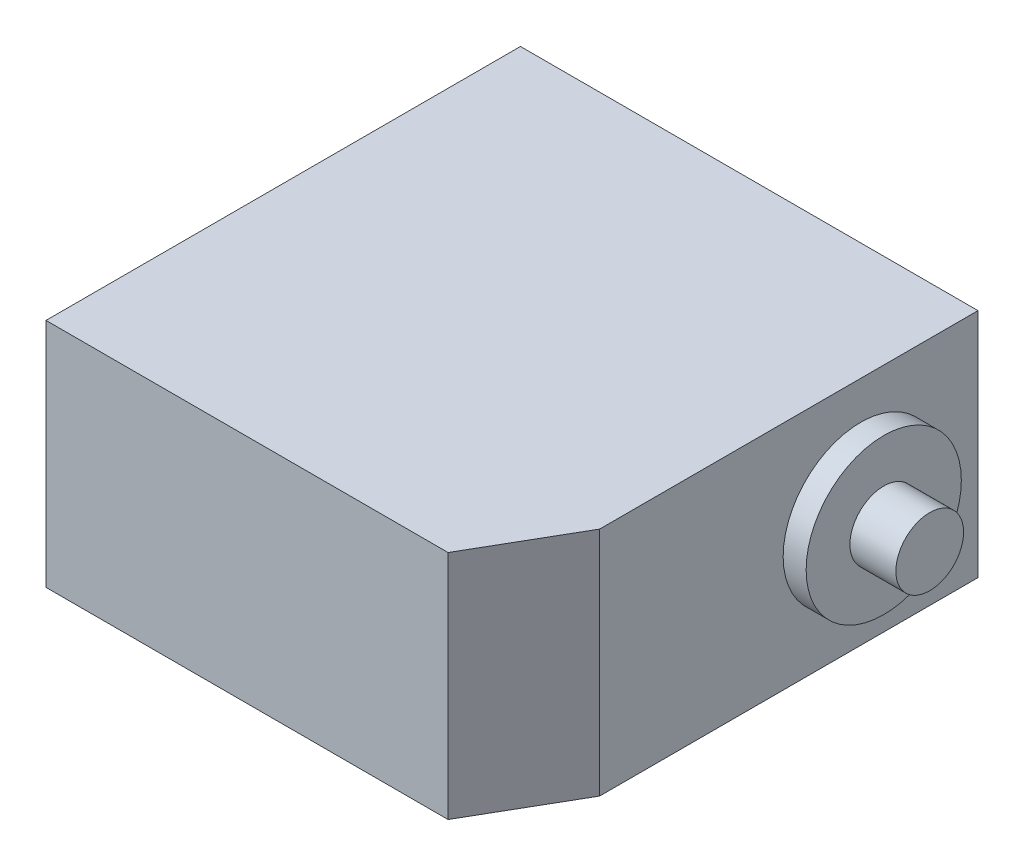
SolidWorks part; units mm, degrees
ref_plane "Front Plane" through (0, 0, 0) normal (0, 0, 1) x (1, 0, 0)
ref_plane "Top Plane" through (0, 0, 0) normal (0, 1, 0) x (1, 0, 0)
ref_plane "Right Plane" through (0, 0, 0) normal (1, 0, 0) x (0, 0, -1)
sketch "Sketch1" plane through (0, 0, 0) normal (0, 1, 0) x (1, 0, 0)
  line L0 (19.9009, -12.2786) -> (15.0749, -20.6375)
  line L1 (-19.9009, -20.6375) -> (15.0749, -20.6375)
  line L2 (-19.9009, -20.6375) -> (-19.9009, 20.6375)
  line L3 (-19.9009, 20.6375) -> (19.9009, 20.6375)
  line L4 (19.9009, -12.2786) -> (19.9009, 20.6375)
  line L5 (-19.9009, -20.6375) -> (19.9009, 20.6375) construction
  line L6 (-19.9009, 20.6375) -> (19.9009, -20.6375) construction
  line L7 (15.0749, -20.6375) -> (19.9009, -20.6375) construction
  line L8 (19.9009, -20.6375) -> (19.9009, -12.2786) construction
  point P0 (0, 0)
  dimension "D1" = 41.275
  dimension "D2" = 39.8018
  dimension "D3" = 60
  dimension "D4" = 4.826
extrude "Boss-Extrude1" add sketch "Sketch1" along normal blind 20.1168
sketch "Sketch2" plane through (19.9009, 0, 0) normal (1, 0, 0) x (0, 0, -1)
  line L0 (20.6375, 10.0584) -> (-12.2786, 10.0584) construction
  line L1 (20.6375, 20.1168) -> (20.6375, 0) construction
  line L2 (-12.2786, 20.1168) -> (-12.2786, 0) construction
  circle A0 centre (10.4375, 10.0584) radius 6.75
  dimension "D1" = 13.5
  dimension "D2" = 3.45
extrude "Boss-Extrude2" add sketch "Sketch2" along normal blind 2
sketch "Sketch3" plane through (21.9009, 0, 0) normal (1, 0, 0) x (0, 0, -1)
  circle A0 centre (10.4375, 10.0584) radius 2.945
  dimension "D1" = 5.89
extrude "Boss-Extrude3" add sketch "Sketch3" along normal blind 4
